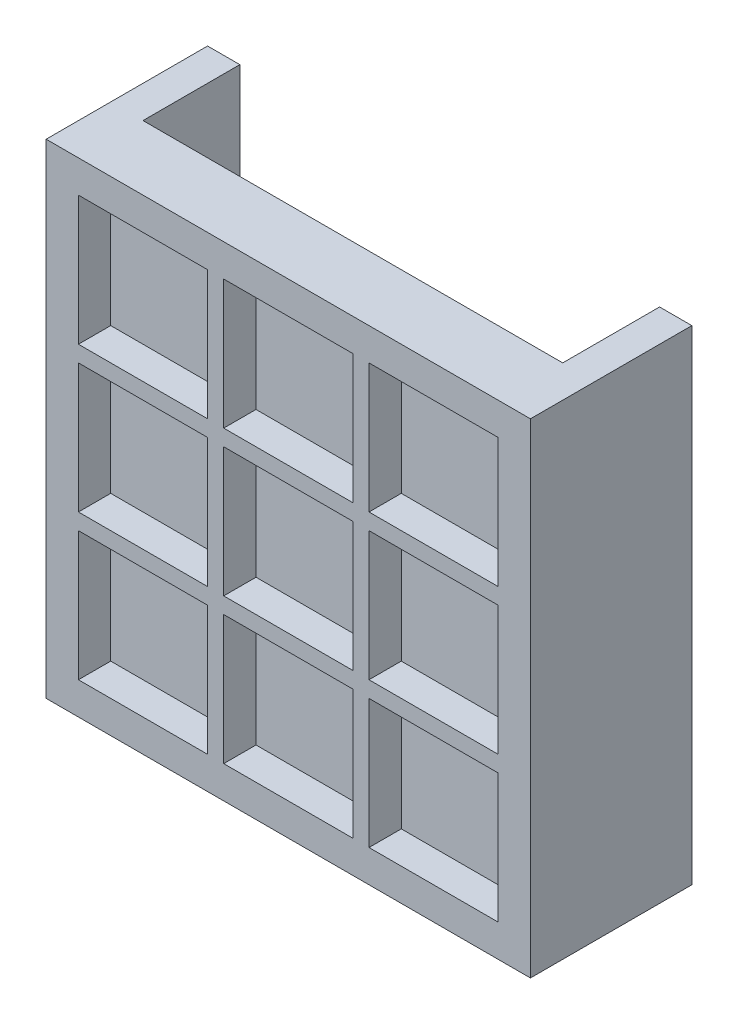
SolidWorks part; units mm, degrees
ref_plane "Front Plane" through (0, 0, 0) normal (0, 0, 1) x (1, 0, 0)
ref_plane "Top Plane" through (0, 0, 0) normal (0, 1, 0) x (1, 0, 0)
ref_plane "Right Plane" through (0, 0, 0) normal (1, 0, 0) x (0, 0, -1)
sketch "Sketch1" plane through (0, 0, 0) normal (0, 0, 1) x (1, 0, 0)
  line L1 (-106.2081, 64.4295) -> (43.7919, 64.4295)
  line L2 (-106.2081, 64.4295) -> (-106.2081, -85.5705)
  line L3 (-106.2081, -85.5705) -> (43.7919, -85.5705)
  line L4 (43.7919, 64.4295) -> (43.7919, -85.5705)
  dimension "D1" = 150
  dimension "D2" = 150
extrude "Boss-Extrude1" add sketch "Sketch1" along normal blind 10
sketch "Sketch2" plane through (0, 0, 10) normal (0, 0, 1) x (1, 0, 0)
  line L0 (-106.2081, -85.5705) -> (43.7919, -85.5705) construction
  line L1 (-106.2081, 64.4295) -> (-96.2081, 64.4295)
  line L2 (-106.2081, 64.4295) -> (-106.2081, -85.5705)
  line L3 (-106.2081, -85.5705) -> (-96.2081, -85.5705)
  line L4 (-96.2081, 64.4295) -> (-96.2081, -85.5705)
  line L5 (43.7919, 64.4295) -> (-106.2081, 64.4295) construction
  line L6 (43.7919, 64.4295) -> (33.7919, 64.4295)
  line L7 (43.7919, 64.4295) -> (43.7919, -85.5705)
  line L8 (43.7919, -85.5705) -> (33.7919, -85.5705)
  line L9 (33.7919, 64.4295) -> (33.7919, -85.5705)
  line L10 (-56.2081, 64.4295) -> (-51.2081, 64.4295)
  line L11 (-56.2081, 64.4295) -> (-56.2081, -85.5705)
  line L12 (-56.2081, -85.5705) -> (-51.2081, -85.5705)
  line L13 (-51.2081, 64.4295) -> (-51.2081, -85.5705)
  line L15 (-11.2081, 64.4295) -> (-6.2081, 64.4295)
  line L16 (-11.2081, 64.4295) -> (-11.2081, -85.5705)
  line L17 (-11.2081, -85.5705) -> (-6.2081, -85.5705)
  line L18 (-6.2081, 64.4295) -> (-6.2081, -85.5705)
  line L19 (-96.2081, 64.4295) -> (-56.2081, 64.4295)
  line L20 (-96.2081, 64.4295) -> (-96.2081, 54.4295)
  line L21 (-96.2081, 54.4295) -> (-56.2081, 54.4295)
  line L22 (-56.2081, 64.4295) -> (-56.2081, 54.4295)
  line L23 (-51.2081, 64.4295) -> (-11.2081, 64.4295)
  line L24 (-51.2081, 64.4295) -> (-51.2081, 54.4295)
  line L25 (-51.2081, 54.4295) -> (-11.2081, 54.4295)
  line L26 (-11.2081, 64.4295) -> (-11.2081, 54.4295)
  line L27 (-6.2081, 64.4295) -> (33.7919, 64.4295)
  line L28 (-6.2081, 64.4295) -> (-6.2081, 54.4295)
  line L29 (-6.2081, 54.4295) -> (33.7919, 54.4295)
  line L30 (33.7919, 64.4295) -> (33.7919, 54.4295)
  line L31 (-96.2081, -85.5705) -> (-56.2081, -85.5705)
  line L32 (-96.2081, -85.5705) -> (-96.2081, -75.5705)
  line L33 (-96.2081, -75.5705) -> (-56.2081, -75.5705)
  line L34 (-56.2081, -85.5705) -> (-56.2081, -75.5705)
  line L35 (-51.2081, -85.5705) -> (-11.2081, -85.5705)
  line L36 (-51.2081, -85.5705) -> (-51.2081, -75.5705)
  line L37 (-51.2081, -75.5705) -> (-11.2081, -75.5705)
  line L38 (-11.2081, -85.5705) -> (-11.2081, -75.5705)
  line L39 (-6.2081, -85.5705) -> (33.7919, -85.5705)
  line L40 (-6.2081, -85.5705) -> (-6.2081, -75.5705)
  line L41 (-6.2081, -75.5705) -> (33.7919, -75.5705)
  line L42 (33.7919, -85.5705) -> (33.7919, -75.5705)
  line L43 (-96.2081, 14.4295) -> (-56.2081, 14.4295)
  line L44 (-96.2081, 14.4295) -> (-96.2081, 9.4295)
  line L45 (-96.2081, 9.4295) -> (-56.2081, 9.4295)
  line L46 (-56.2081, 14.4295) -> (-56.2081, 9.4295)
  line L47 (-51.2081, 14.4295) -> (-11.2081, 14.4295)
  line L48 (-51.2081, 14.4295) -> (-51.2081, 9.4295)
  line L49 (-51.2081, 9.4295) -> (-11.2081, 9.4295)
  line L50 (-11.2081, 14.4295) -> (-11.2081, 9.4295)
  line L51 (-6.2081, 14.4295) -> (33.7919, 14.4295)
  line L52 (-6.2081, 14.4295) -> (-6.2081, 9.4295)
  line L53 (-6.2081, 9.4295) -> (33.7919, 9.4295)
  line L54 (33.7919, 14.4295) -> (33.7919, 9.4295)
  line L55 (-96.2081, -30.5705) -> (-56.2081, -30.5705)
  line L56 (-96.2081, -30.5705) -> (-96.2081, -35.5705)
  line L57 (-96.2081, -35.5705) -> (-56.2081, -35.5705)
  line L58 (-56.2081, -30.5705) -> (-56.2081, -35.5705)
  line L59 (-51.2081, -30.5705) -> (-11.2081, -30.5705)
  line L60 (-51.2081, -30.5705) -> (-51.2081, -35.5705)
  line L61 (-51.2081, -35.5705) -> (-11.2081, -35.5705)
  line L62 (-11.2081, -30.5705) -> (-11.2081, -35.5705)
  line L63 (-6.2081, -30.5705) -> (33.7919, -30.5705)
  line L64 (-6.2081, -30.5705) -> (-6.2081, -35.5705)
  line L65 (-6.2081, -35.5705) -> (33.7919, -35.5705)
  line L66 (33.7919, -30.5705) -> (33.7919, -35.5705)
  line M35 (-106.2081, 64.4295) -> (-106.2081, -85.5705)
  line M36 (-106.2081, -85.5705) -> (43.7919, -85.5705)
  line M37 (43.7919, -85.5705) -> (43.7919, 64.4295)
  line M38 (43.7919, 64.4295) -> (-106.2081, 64.4295)
  dimension "D1" = 10
  dimension "D2" = 5
  dimension "D3" = 5
  dimension "D4" = 10
  dimension "D5" = 40
  dimension "D6" = 40
  dimension "D7" = 40
  dimension "D8" = 10
  dimension "D9" = 10
  dimension "D10" = 10
  dimension "D11" = 10
  dimension "D12" = 10
  dimension "D13" = 10
  dimension "D14" = 40
  dimension "D15" = 40
  dimension "D16" = 40
  dimension "D17" = 5
  dimension "D18" = 5
  dimension "D19" = 5
  dimension "D20" = 40
  dimension "D21" = 40
  dimension "D22" = 40
  dimension "D23" = 5
  dimension "D24" = 5
  dimension "D25" = 5
  dimension "D26" = 40
  dimension "D27" = 40
  dimension "D28" = 40
  dimension "D29" = 40
  dimension "D30" = 40
  dimension "D31" = 40
extrude "Boss-Extrude2" add sketch "Sketch2" along normal blind 10 contours L4 M38 M35 M36 | L4 L45 L11 L43 | L13 L11 M38 M36 | L4 L21 L11 M38 | L13 L25 L16 M38 | L18 L16 M38 M36 | L18 L29 L9 M38 | L9 M38 M36 M37 | L33 L4 L11 M36 | L41 L18 L9 M36 | L37 L13 L16 M36 | L47 L50 L49 L48 | L51 L54 L53 L52 | L63 L66 L65 L64 | L57 L58 L55 L56 | L59 L62 L61 L60
sketch "Sketch3" plane through (0, 0, 10) normal (0, 0, 1) x (1, 0, 0)
  line L0 (-56.2081, 54.4295) -> (-56.2081, 14.4295) construction
  line L1 (-96.2081, 54.4295) -> (-56.2081, 54.4295)
  line L2 (-96.2081, 54.4295) -> (-96.2081, 49.4295)
  line L3 (-96.2081, 49.4295) -> (-56.2081, 49.4295)
  line L4 (-56.2081, 54.4295) -> (-56.2081, 49.4295)
  line L5 (-11.2081, 54.4295) -> (-11.2081, 14.4295) construction
  line L6 (-51.2081, 54.4295) -> (-11.2081, 54.4295)
  line L7 (-51.2081, 54.4295) -> (-51.2081, 49.4295)
  line L8 (-51.2081, 49.4295) -> (-11.2081, 49.4295)
  line L9 (-11.2081, 54.4295) -> (-11.2081, 49.4295)
  line L10 (33.7919, 54.4295) -> (33.7919, 14.4295) construction
  line L11 (-6.2081, 54.4295) -> (33.7919, 54.4295)
  line L12 (-6.2081, 54.4295) -> (-6.2081, 49.4295)
  line L13 (-6.2081, 49.4295) -> (33.7919, 49.4295)
  line L14 (33.7919, 54.4295) -> (33.7919, 49.4295)
  line L15 (-56.2081, 9.4295) -> (-56.2081, -30.5705) construction
  line L16 (-96.2081, 9.4295) -> (-56.2081, 9.4295)
  line L17 (-96.2081, 9.4295) -> (-96.2081, 4.4295)
  line L18 (-96.2081, 4.4295) -> (-56.2081, 4.4295)
  line L19 (-56.2081, 9.4295) -> (-56.2081, 4.4295)
  line L20 (-11.2081, 9.4295) -> (-11.2081, -30.5705) construction
  line L21 (-51.2081, 9.4295) -> (-11.2081, 9.4295)
  line L22 (-51.2081, 9.4295) -> (-51.2081, 4.4295)
  line L23 (-51.2081, 4.4295) -> (-11.2081, 4.4295)
  line L24 (-11.2081, 9.4295) -> (-11.2081, 4.4295)
  line L25 (33.7919, 9.4295) -> (33.7919, -30.5705) construction
  line L26 (-6.2081, 9.4295) -> (33.7919, 9.4295)
  line L27 (-6.2081, 9.4295) -> (-6.2081, 4.4295)
  line L28 (-6.2081, 4.4295) -> (33.7919, 4.4295)
  line L29 (33.7919, 9.4295) -> (33.7919, 4.4295)
  line L30 (-56.2081, -35.5705) -> (-56.2081, -75.5705) construction
  line L31 (-96.2081, -35.5705) -> (-56.2081, -35.5705)
  line L32 (-96.2081, -35.5705) -> (-96.2081, -40.5705)
  line L33 (-96.2081, -40.5705) -> (-56.2081, -40.5705)
  line L34 (-56.2081, -35.5705) -> (-56.2081, -40.5705)
  line L35 (-11.2081, -35.5705) -> (-11.2081, -75.5705) construction
  line L36 (-51.2081, -35.5705) -> (-11.2081, -35.5705)
  line L37 (-51.2081, -35.5705) -> (-51.2081, -40.5705)
  line L38 (-51.2081, -40.5705) -> (-11.2081, -40.5705)
  line L39 (-11.2081, -35.5705) -> (-11.2081, -40.5705)
  line L40 (33.7919, -35.5705) -> (33.7919, -75.5705) construction
  line L41 (-6.2081, -35.5705) -> (33.7919, -35.5705)
  line L42 (-6.2081, -35.5705) -> (-6.2081, -40.5705)
  line L43 (-6.2081, -40.5705) -> (33.7919, -40.5705)
  line L44 (33.7919, -35.5705) -> (33.7919, -40.5705)
  dimension "D1" = 5
  dimension "D2" = 5
  dimension "D3" = 5
  dimension "D4" = 5
  dimension "D5" = 5
  dimension "D6" = 5
  dimension "D7" = 5
  dimension "D8" = 5
  dimension "D9" = 5
extrude "Cut-Extrude1" cut sketch "Sketch3" against normal blind 10 contours L17 L16 L19 L18 | L2 L1 L4 L3 | L32 L31 L34 L33 | L22 L21 L24 L23 | L7 L6 L9 L8 | L37 L36 L39 L38 | L42 L41 L44 L43 | L27 L26 L29 L28 | L12 L11 L14 L13
sketch "Sketch4" plane through (0, 0, 0) normal (0, 0, -1) x (-1, 0, 0)
  line L0 (106.2081, -85.5705) -> (-43.7919, -85.5705) construction
  line L1 (-43.7919, 64.4295) -> (-33.7919, 64.4295)
  line L2 (-43.7919, 64.4295) -> (-43.7919, -85.5705)
  line L3 (-43.7919, -85.5705) -> (-33.7919, -85.5705)
  line L4 (-33.7919, 64.4295) -> (-33.7919, -85.5705)
  line L6 (106.2081, 64.4295) -> (96.2081, 64.4295)
  line L7 (106.2081, 64.4295) -> (106.2081, -85.5705)
  line L8 (106.2081, -85.5705) -> (96.2081, -85.5705)
  line L9 (96.2081, 64.4295) -> (96.2081, -85.5705)
  dimension "D1" = 10
  dimension "D2" = 10
extrude "Boss-Extrude3" add sketch "Sketch4" along normal blind 30
